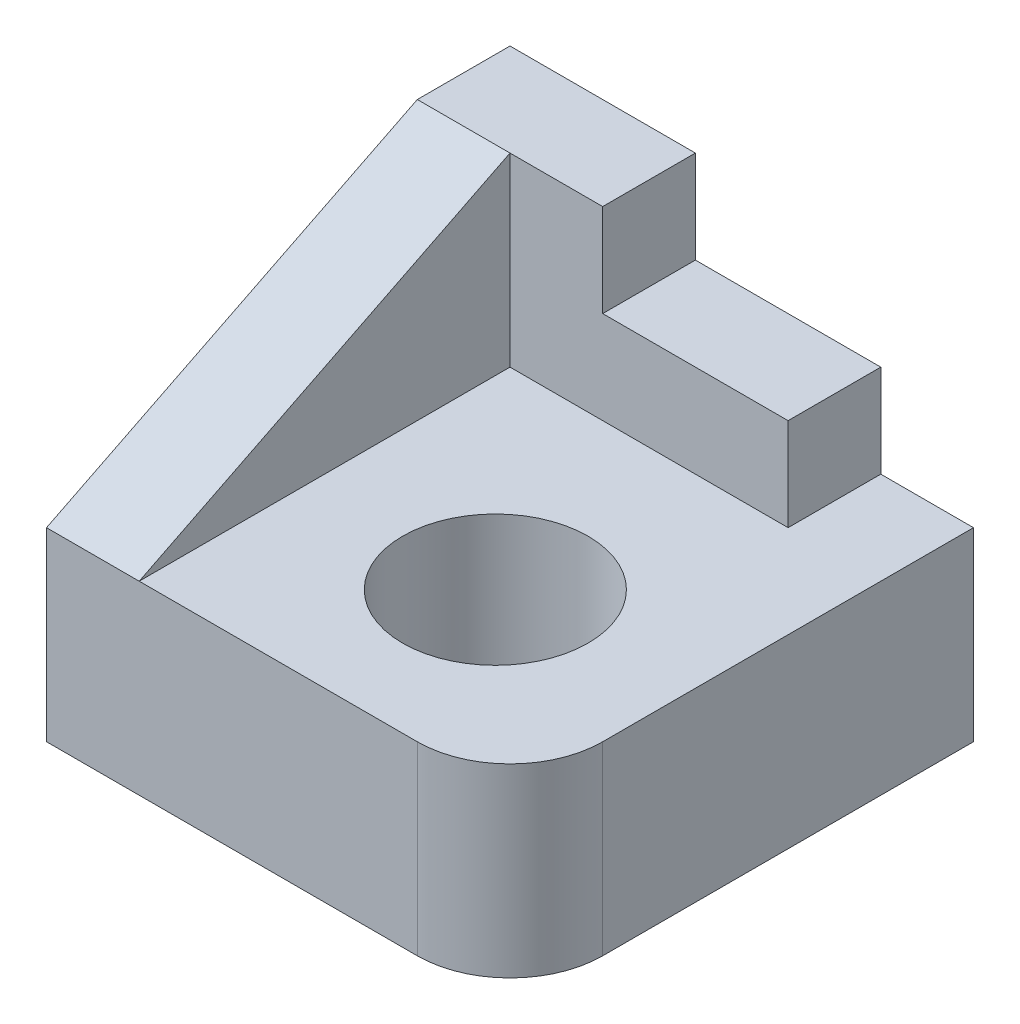
SolidWorks part; units mm, degrees
ref_plane "Front Plane" through (0, 0, 0) normal (0, 0, 1) x (1, 0, 0)
ref_plane "Top Plane" through (0, 0, 0) normal (0, 1, 0) x (1, 0, 0)
ref_plane "Right Plane" through (0, 0, 0) normal (1, 0, 0) x (0, 0, -1)
sketch "Sketch1" plane through (0, 0, 0) normal (0, 1, 0) x (1, 0, 0)
  line L1 (-30, 31.581) -> (20, 31.581)
  line L2 (-30, 31.581) -> (-30, -18.419)
  line L3 (-30, -18.419) -> (10, -18.419)
  line L4 (20, 31.581) -> (20, -8.419)
  circle A0 centre (0, 0) radius 10
  arc A2 (10, -18.419) -> (20, -8.419) centre (10, -8.419) ccw
  dimension "D1" = 20
  dimension "D5" = 10
  dimension "D2" = 20
  dimension "D3" = 50
  dimension "D4" = 50
extrude "Boss-Extrude1" add sketch "Sketch1" along normal blind 20
sketch "Sketch2" plane through (-30, 0, 0) normal (-1, 0, 0) x (0, 0, 1)
  line L0 (18.419, 20) -> (-21.581, 20)
  line L1 (-31.581, 20) -> (18.419, 20) construction
  line L2 (-21.581, 20) -> (-21.581, 40)
  line L3 (-21.581, 40) -> (18.419, 20)
  dimension "D1" = 40
  dimension "D2" = 20
extrude "Boss-Extrude2" add sketch "Sketch2" against normal blind 10
sketch "Sketch3" plane through (0, 0, -31.581) normal (0, 0, -1) x (-1, 0, 0)
  line L0 (30, 20) -> (30, 40)
  line L1 (30, 40) -> (10, 40)
  line L2 (10, 40) -> (10, 30)
  line L3 (10, 30) -> (-10, 30)
  line L4 (-10, 30) -> (-10, 20)
  line L5 (-20, 20) -> (30, 20) construction
  line L6 (-10, 20) -> (30, 20)
  dimension "D1" = 20
  dimension "D2" = 20
  dimension "D3" = 10
extrude "Boss-Extrude3" add sketch "Sketch3" against normal blind 10 contours L0 L1 L2 L3 L4 L6
